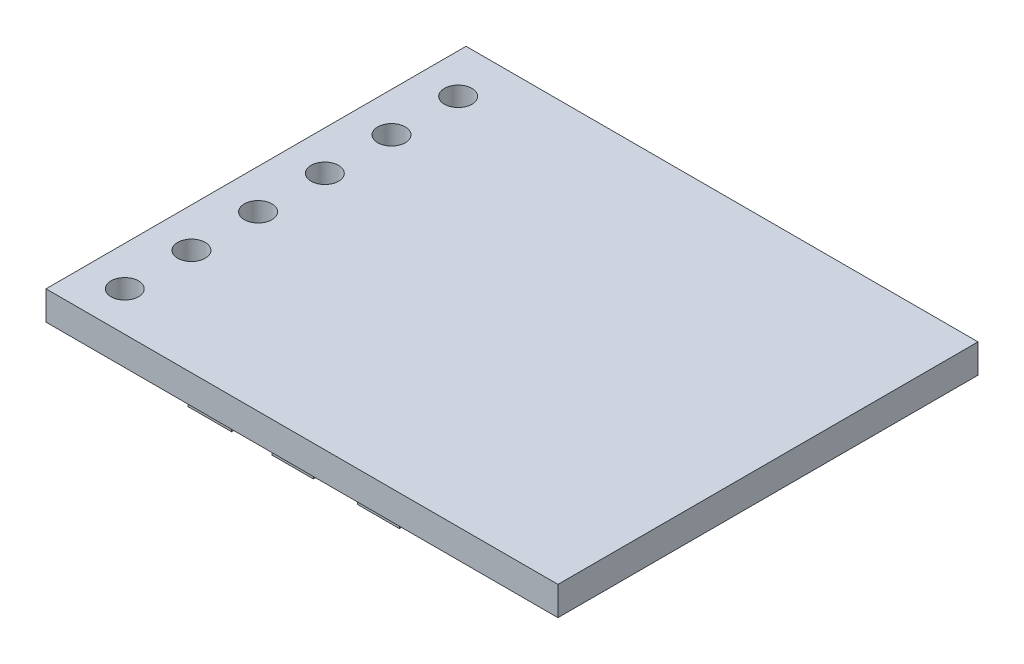
SolidWorks part; units mm, degrees
ref_plane "Front Plane" through (0, 0, 0) normal (0, 0, 1) x (1, 0, 0)
ref_plane "Top Plane" through (0, 0, 0) normal (0, 1, 0) x (1, 0, 0)
ref_plane "Right Plane" through (0, 0, 0) normal (1, 0, 0) x (0, 0, -1)
sketch "Sketch1" plane through (0, 0, 0) normal (0, 1, 0) x (1, 0, 0)
  line L1 (-9.75, 8) -> (9.75, 8)
  line L2 (-9.75, 8) -> (-9.75, -8)
  line L3 (-9.75, -8) -> (9.75, -8)
  line L4 (9.75, 8) -> (9.75, -8)
  line L5 (-9.75, 8) -> (9.75, -8) construction
  line L6 (-9.75, -8) -> (9.75, 8) construction
  point P0 (0, 0)
  dimension "D1" = 19.5
  dimension "D2" = 16
extrude "PCB" add sketch "Sketch1" along normal blind 1.1
sketch "Sketch2" plane through (0, 1.1, 0) normal (0, 1, 0) x (1, 0, 0)
  line L0 (-8.25, 8) -> (-8.25, -8) construction
  line L1 (9.75, 8) -> (-9.75, 8) construction
  line L2 (-9.75, -8) -> (9.75, -8) construction
  line L3 (-9.75, 8) -> (-9.75, -8) construction
  circle A0 centre (-8.25, -6.5) radius 0.525
  circle A1 centre (-8.25, -3.96) radius 0.525
  circle A2 centre (-8.25, -1.42) radius 0.525
  circle A3 centre (-8.25, 1.12) radius 0.525
  circle A4 centre (-8.25, 3.66) radius 0.525
  circle A5 centre (-8.25, 6.2) radius 0.525
  point P10 (0, 0)
  dimension "D1" = 1.05
  dimension "D5" = 2.54
  dimension "D2" = 1.5
  dimension "D3" = 1.5
  dimension "D4" = 6
extrude "Holes" cut sketch "Sketch2" against normal up to next
sketch "Sketch3" plane through (0, 0, 0) normal (0, -1, 0) x (1, 0, 0)
  line L1 (-2.8189, 4.1517) -> (4.1517, 4.1517)
  line L2 (-2.8189, 4.1517) -> (-2.8189, -2.8955)
  line L3 (-2.8189, -2.8955) -> (4.1517, -2.8955)
  line L4 (4.1517, 4.1517) -> (4.1517, -2.8955)
  line L5 (-6.0514, -4.259) -> (-2.8189, -4.259)
  line L6 (-6.0514, -4.259) -> (-6.0514, -6.1127)
  line L7 (-6.0514, -6.1127) -> (-2.8189, -6.1127)
  line L8 (-2.8189, -4.259) -> (-2.8189, -6.1127)
  line L9 (-1.8384, -4.9637) -> (-0.2298, -4.9637)
  line L10 (-1.8384, -4.9637) -> (-1.8384, -5.6378)
  line L11 (-1.8384, -5.6378) -> (-0.2298, -5.6378)
  line L12 (-0.2298, -4.9637) -> (-0.2298, -5.6378)
  line L13 (-1.8384, -5.8829) -> (-0.2298, -5.8829)
  line L14 (-1.8384, -5.8829) -> (-1.8384, -6.6489)
  line L15 (-1.8384, -6.6489) -> (-0.2298, -6.6489)
  line L16 (-0.2298, -5.8829) -> (-0.2298, -6.6489)
  line L17 (0.812, -5.4999) -> (3.9526, -5.4999)
  line L18 (0.812, -5.4999) -> (0.812, -6.9706)
  line L19 (0.812, -6.9706) -> (3.9526, -6.9706)
  line L20 (3.9526, -5.4999) -> (3.9526, -6.9706)
  line L21 (4.4735, 6.6489) -> (5.4233, 6.6489)
  line L22 (4.4735, 6.6489) -> (4.4735, 5.2854)
  line L23 (4.4735, 5.2854) -> (5.4233, 5.2854)
  line L24 (5.4233, 6.6489) -> (5.4233, 5.2854)
  line L25 (5.8063, 6.6489) -> (6.7255, 6.6489)
  line L26 (5.8063, 6.6489) -> (5.8063, 5.2854)
  line L27 (5.8063, 5.2854) -> (6.7255, 5.2854)
  line L28 (6.7255, 6.6489) -> (6.7255, 5.2854)
  line L29 (2.7423, 7.0319) -> (1.149, 7.0319)
  line L30 (2.7423, 7.0319) -> (2.7423, 6.2046)
  line L31 (2.7423, 6.2046) -> (1.149, 6.2046)
  line L32 (1.149, 7.0319) -> (1.149, 6.2046)
  line L33 (-0.5362, 7.0319) -> (-2.1142, 7.0319)
  line L34 (-0.5362, 7.0319) -> (-0.5362, 6.2046)
  line L35 (-0.5362, 6.2046) -> (-2.1142, 6.2046)
  line L36 (-2.1142, 7.0319) -> (-2.1142, 6.2046)
  line L37 (-3.6462, 7.0319) -> (-5.3161, 7.0319)
  line L38 (-3.6462, 7.0319) -> (-3.6462, 6.2046)
  line L39 (-3.6462, 6.2046) -> (-5.3161, 6.2046)
  line L40 (-5.3161, 7.0319) -> (-5.3161, 6.2046)
  line L41 (4.4735, -4.9637) -> (5.5152, -4.9637)
  line L42 (4.4735, -4.9637) -> (4.4735, -6.4804)
  line L43 (4.4735, -6.4804) -> (5.5152, -6.4804)
  line L44 (5.5152, -4.9637) -> (5.5152, -6.4804)
  line L45 (5.9442, -4.9637) -> (6.8787, -4.9637)
  line L46 (5.9442, -4.9637) -> (5.9442, -6.4804)
  line L47 (5.9442, -6.4804) -> (6.8787, -6.4804)
  line L48 (6.8787, -4.9637) -> (6.8787, -6.4804)
extrude "Bottom components" add sketch "Sketch3" along normal blind 1.05
